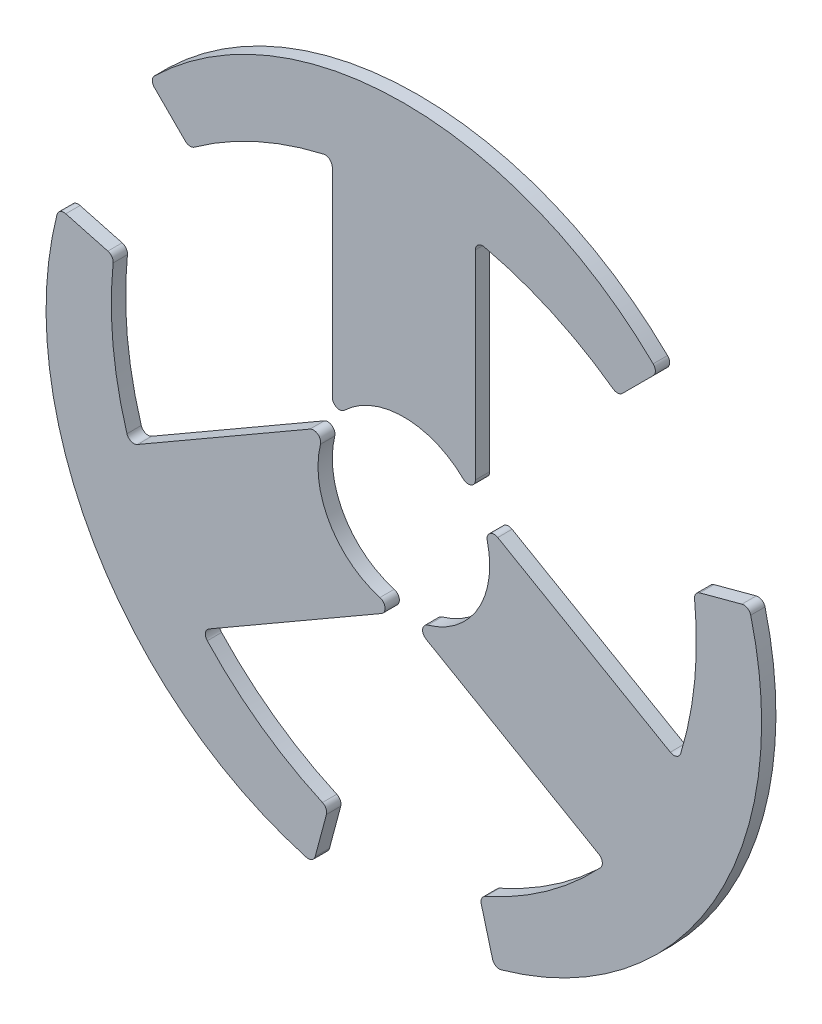
SolidWorks part; units mm, degrees
ref_plane "Front Plane" through (0, 0, 0) normal (0, 0, 1) x (1, 0, 0)
ref_plane "Top Plane" through (0, 0, 0) normal (0, 1, 0) x (1, 0, 0)
ref_plane "Right Plane" through (0, 0, 0) normal (1, 0, 0) x (0, 0, -1)
sketch "Sketch1" plane through (0, 0, 0) normal (0, 0, 1) x (1, 0, 0)
  line L0 (-39.7176, 82.9924) -> (-39.7176, 177.9924) construction
  line L1 (28.3744, -15.1934) -> (-31.9137, 19.6139)
  line L2 (-14.713, 146.0547) -> (-14.713, 76.44)
  line L3 (-64.7223, 146.0547) -> (-64.7223, 76.44)
  line L4 (-114.3623, 126.7922) -> (-114.571, 126.7922)
  line L5 (-127.5882, 140.863) -> (-60.99, 74.2648) construction
  line L6 (-18.4452, 74.2648) -> (48.153, 140.863) construction
  line L7 (36.6534, 128.31) -> (47.4208, 139.0774)
  line L8 (53.379, 28.1159) -> (-6.9091, 62.9233)
  line L9 (63.6948, 81.4729) -> (78.4033, 85.4141)
  line L10 (-116.0887, 128.31) -> (-126.8561, 139.0774)
  line L11 (-12.6762, -50.8057) -> (-8.7351, -65.5142)
  line L12 (-132.8143, 28.1159) -> (-72.5262, 62.9233)
  line L13 (-107.8096, -15.1934) -> (-47.5215, 19.6139)
  line L14 (-66.759, -50.8057) -> (-70.7002, -65.5142)
  line L15 (-143.1301, 81.4729) -> (-157.8386, 85.4141)
  arc A0 (33.4229, 128.0504) -> (-11.6517, 148.4909) centre (-39.7176, 26.6824) ccw
  arc A1 (47.3953, 142.638) -> (-126.8306, 142.638) centre (-39.7176, 52.9924) ccw
  arc A2 (-18.9441, 74.6364) -> (-60.4912, 74.6364) centre (-39.7176, 52.9924) ccw
  arc A3 (-14.713, 76.44) -> (-18.9441, 74.6364) centre (-17.213, 76.44) cw
  arc A4 (-64.7223, 76.44) -> (-60.4912, 74.6364) centre (-62.2223, 76.44) ccw
  arc A5 (-67.7836, 148.4909) -> (-112.8581, 128.0504) centre (-39.7176, 26.6824) ccw
  arc A6 (36.6534, 128.31) -> (33.4229, 128.0504) centre (34.8857, 130.0778) cw
  arc A7 (47.4208, 139.0774) -> (47.3953, 142.638) centre (45.653, 140.8451) ccw
  arc A8 (-126.8561, 139.0774) -> (-126.8306, 142.638) centre (-125.0883, 140.8451) cw
  arc A9 (-116.0887, 128.31) -> (-112.8581, 128.0504) centre (-114.3209, 130.0778) ccw
  arc A10 (-11.6517, 148.4909) -> (-14.713, 146.0547) centre (-12.213, 146.0547) ccw
  arc A11 (-64.7223, 146.0547) -> (-67.7836, 148.4909) centre (-67.2223, 146.0547) ccw
  circle A13 centre (-110.3279, 143.7624) radius 1.25
  circle A14 centre (30.8926, 143.7624) radius 1.25
  circle A15 centre (-39.7176, 92.9924) radius 1.25
  arc A16 (28.9535, -19.0627) -> (28.3744, -15.1934) centre (27.1244, -17.3585) ccw
  arc A17 (-31.9137, 19.6139) -> (-31.3602, 24.18) centre (-30.6637, 21.779) cw
  arc A18 (-31.3602, 24.18) -> (-10.5867, 60.1608) centre (-39.7176, 52.9924) ccw
  arc A19 (-6.9091, 62.9233) -> (-10.5867, 60.1608) centre (-8.1591, 60.7582) ccw
  arc A20 (53.379, 28.1159) -> (57.0194, 29.549) centre (54.629, 30.281) ccw
  arc A21 (57.0194, 29.549) -> (61.8547, 78.805) centre (-62.5028, 66.1474) ccw
  arc A22 (63.6948, 81.4729) -> (61.8547, 78.805) centre (64.3419, 79.0581) ccw
  arc A23 (78.4033, 85.4141) -> (81.4742, 83.6116) centre (79.0504, 82.9992) cw
  arc A24 (-5.6387, -67.2724) -> (81.4742, 83.6116) centre (-39.7176, 52.9924) ccw
  arc A25 (-8.7351, -65.5142) -> (-5.6387, -67.2724) centre (-6.3203, -64.8671) ccw
  arc A26 (-12.6762, -50.8057) -> (-11.2858, -47.8781) centre (-10.2614, -50.1586) cw
  arc A27 (-11.2858, -47.8781) -> (28.9535, -19.0627) centre (-62.5028, 66.1474) ccw
  arc A28 (-136.4547, 29.549) -> (-132.8143, 28.1159) centre (-134.0643, 30.281) ccw
  arc A29 (-72.5262, 62.9233) -> (-68.8486, 60.1608) centre (-71.2762, 60.7582) cw
  arc A30 (-68.8486, 60.1608) -> (-48.0751, 24.18) centre (-39.7176, 52.9924) ccw
  arc A31 (-47.5215, 19.6139) -> (-48.0751, 24.18) centre (-48.7715, 21.779) ccw
  arc A32 (-107.8096, -15.1934) -> (-108.3887, -19.0627) centre (-106.5596, -17.3585) ccw
  arc A33 (-108.3887, -19.0627) -> (-68.1495, -47.8781) centre (-16.9325, 66.1474) ccw
  arc A34 (-66.759, -50.8057) -> (-68.1495, -47.8781) centre (-69.1738, -50.1586) ccw
  arc A35 (-70.7002, -65.5142) -> (-73.7965, -67.2724) centre (-73.115, -64.8671) cw
  arc A36 (-160.9095, 83.6116) -> (-73.7965, -67.2724) centre (-39.7176, 52.9924) ccw
  arc A37 (-157.8386, 85.4141) -> (-160.9095, 83.6116) centre (-158.4856, 82.9992) ccw
  arc A38 (-143.1301, 81.4729) -> (-141.29, 78.805) centre (-143.7771, 79.0581) cw
  arc A39 (-141.29, 78.805) -> (-136.4547, 29.549) centre (-16.9325, 66.1474) ccw
  point P9 (-42.8309, 76.2572)
  point P18 (-39.7176, 132.0448)
  point P21 (-114.571, 126.7922)
  point P46 (-63.2026, 74.1403)
  point P51 (-16.2326, 74.1403)
  point P56 (-39.7176, 82.9924)
  point P99 (-39.7176, 52.9924)
  dimension "D1" = 125
  dimension "D2" = 125
  dimension "D4" = 15
  dimension "D7" = 2.5
  dimension "D10" = 2.5
  dimension "D5" = 3
  dimension "D12" = 2.5
  dimension "D15" = 45
  dimension "D9" = 2.5
  dimension "D3" = 10
  dimension "D16" = 46.97
extrude "Boss-Extrude2" add sketch "Sketch1" along normal blind 5 separate body contours A39 A38 L15 A37 A36 A35 L14 A34 A33 A32 L13 A31 A30 A29 L12 A28 | A27 A26 L11 A25 A24 A23 L9 A22 A21 A20 L8 A19 A18 A17 L1 A16 | A10 L2 A3 A2 A4 L3 A11 A5 A9 L10 A8 A1 A7 L7 A6 A0
